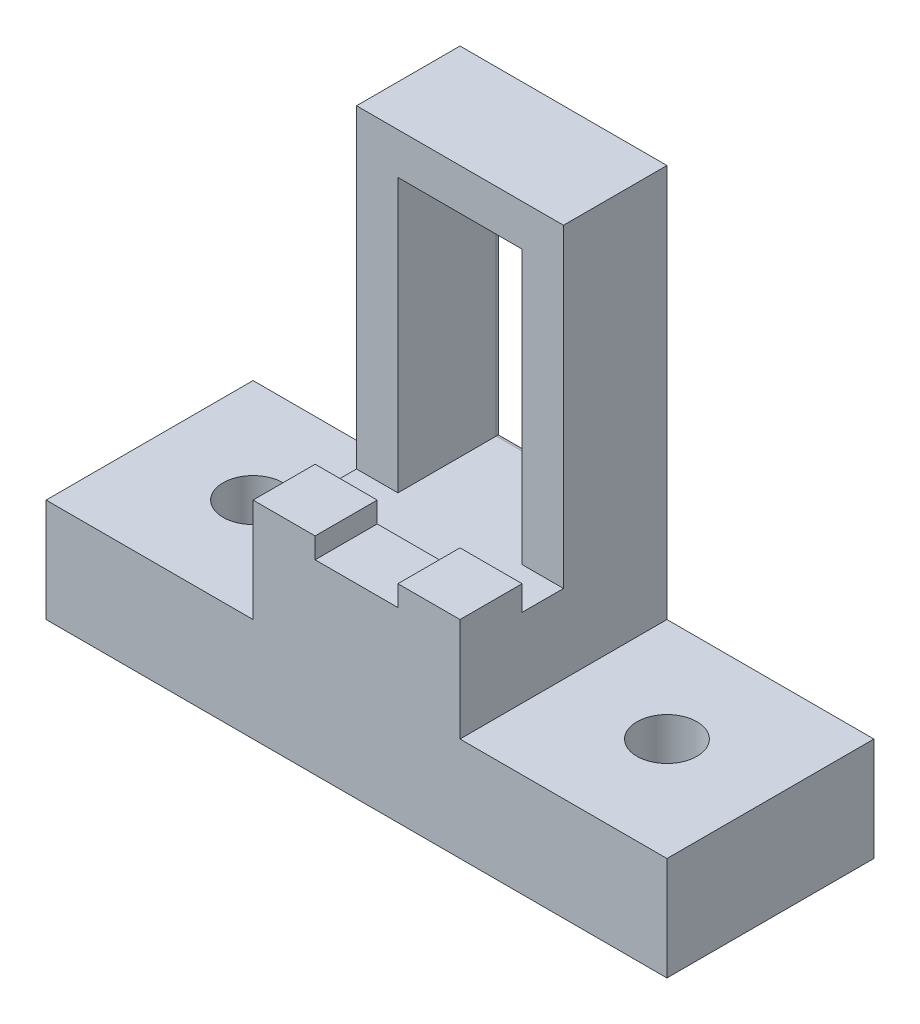
SolidWorks part; units mm, degrees
other "标注1"
sketch "草图8" plane through (-30, 24, -10.05) normal (-0.0333, 0.0376, -0.9987) x (-0.9561, 0.2897, 0.0428)
sketch "草图10" plane through (-30, 24, -10.05) normal (-0.0333, 0.0376, -0.9987) x (-0.9561, 0.2897, 0.0428)
sketch "草图23" plane through (-30, 24, -10) normal (-0.0333, 0.0376, -0.9987) x (-0.9561, 0.2897, 0.0428)
sketch "草图26" plane through (-30, 24, -10) normal (-0.0333, 0.0376, -0.9987) x (-0.9561, 0.2897, 0.0428)
sketch "草图30" plane through (-30, 24, -10) normal (-0.0333, 0.0376, -0.9987) x (-0.9561, 0.2897, 0.0428)
other "标注2"
sketch "草图16" plane through (0, 24, 0) normal (0.8795, 0.3038, 0.3663) x (0.4513, -0.2881, -0.8446)
sketch "草图24" plane through (0, 24, 0) normal (0.8795, 0.3038, 0.3663) x (0.4513, -0.2881, -0.8446)
sketch "草图27" plane through (0, 24, 0) normal (0.8795, 0.3038, 0.3663) x (0.4513, -0.2881, -0.8446)
sketch "草图31" plane through (0, 24, 0) normal (0.8795, 0.3038, 0.3663) x (0.4513, -0.2881, -0.8446)
other "标注3"
sketch "草图17" plane through (0, 24, 0) normal (0.8795, 0.3038, 0.3663) x (0.4513, -0.2881, -0.8446)
sketch "草图25" plane through (0, 24, 0) normal (0.8795, 0.3038, 0.3663) x (0.4513, -0.2881, -0.8446)
sketch "草图28" plane through (0, 24, 0) normal (0.8795, 0.3038, 0.3663) x (0.4513, -0.2881, -0.8446)
sketch "草图32" plane through (0, 24, 0) normal (0.8795, 0.3038, 0.3663) x (0.4513, -0.2881, -0.8446)
ref_plane "前视基准面" through (0, 0, 0) normal (0, 0, 1) x (1, 0, 0)
ref_plane "上视基准面" through (0, 0, 0) normal (0, 1, 0) x (1, 0, 0)
ref_plane "右视基准面" through (0, 0, 0) normal (1, 0, 0) x (0, 0, -1)
other "Configuration Table"
sketch "草图1" plane through (0, 0, 0) normal (0, 1, 0) x (1, 0, 0)
  line L0 (-20, 0) -> (-20, -5)
  line L2 (0, 0) -> (0, 10)
  line L3 (0, 10) -> (-30, 10)
  line L4 (-30, 0) -> (-30, 10)
  line L5 (-20, -5) -> (-10, -5)
  line L6 (-10, -5) -> (-10, 0)
  line L7 (-30, 0) -> (-20, 0)
  line L8 (-10, 0) -> (0, 0)
  dimension "D1" = 10
  dimension "D2" = 30
  dimension "D3" = 10
  dimension "D4" = 10
  dimension "D5" = 5
  dimension "D6" = 5
extrude "凸台-拉伸1" add sketch "草图1" along normal blind 4
sketch "草图2" plane through (0, 4, 0) normal (0, 1, 0) x (1, 0, 0)
  line L7 (0, 10) -> (-30, 10) construction
  line L8 (-20, -5) -> (-10, -5)
  line L9 (-20, -5) -> (-20, 10)
  line L10 (-20, 10) -> (-10, 10)
  line L11 (-10, -5) -> (-10, 10)
extrude "凸台-拉伸2" add sketch "草图2" along normal blind 20
sketch "草图3" plane through (0, 4, 0) normal (0, 1, 0) x (1, 0, 0)
  line L0 (-20, 10) -> (-30, 10) construction
  line L1 (-30, 10) -> (-30, 0) construction
  line L2 (0, 10) -> (-10, 10) construction
  line L3 (0, 0) -> (0, 10) construction
  circle A0 centre (-25, 5) radius 1.45
  circle A1 centre (-5, 5) radius 1.45
  dimension "D1" = 5
  dimension "D2" = 5
  dimension "D3" = 5
  dimension "D4" = 5
  dimension "D5" = 2.9
  dimension "D6" = 2.9
extrude "切除-拉伸1" cut sketch "草图3" against normal blind 20
sketch "草图4" plane through (0, 0, -10) normal (0, 0, -1) x (-1, 0, 0)
  line L6 (10, 24) -> (10, 4) construction
  line L7 (12, 22) -> (18, 22)
  line L8 (12, 22) -> (12, 8.8)
  line L9 (12, 8.8) -> (18, 8.8)
  line L10 (18, 22) -> (18, 8.8)
  line L11 (10, 24) -> (20, 24) construction
  dimension "D1" = 6
  dimension "D2" = 13.2
  dimension "D3" = 2
  dimension "D4" = 2
extrude "切除-拉伸2" cut sketch "草图4" against normal blind 9.5
sketch "草图6" plane through (0, 0, -0.5) normal (0, 0, -1) x (-1, 0, 0)
  line L0 (15, 22) -> (15, 20.68) construction
  line L1 (18, 22) -> (12, 22) construction
  line L2 (15, 20.68) -> (15, 15.6) construction
  line L3 (15, 15.6) -> (15, 10.52) construction
  circle A0 centre (15, 20.68) radius 0.75
  circle A2 centre (15, 10.52) radius 0.75
  circle A3 centre (15, 15.6) radius 0.75
  dimension "D4" = 1.5
  dimension "D5" = 1.5
  dimension "D6" = 1.5
  dimension "D1" = 1.32
  dimension "D2" = 5.08
  dimension "D3" = 5.08
extrude "切除-拉伸4" cut sketch "草图6" against normal blind 3.5
sketch "草图7" plane through (0, 0, 5) normal (0, 0, 1) x (1, 0, 0)
  line L4 (-10, 24) -> (-20, 24)
  line L5 (-20, 24) -> (-20, 0)
  line L6 (-20, 0) -> (-10, 0)
  line L7 (-10, 0) -> (-10, 24)
  line L8 (-10, 24) -> (-20, 24)
  line L9 (-20, 24) -> (-20, 0)
  line L10 (-20, 0) -> (-10, 0)
  line L11 (-10, 0) -> (-10, 24)
  dimension "D1" = 0
extrude "切除-拉伸5" cut sketch "草图7" against normal blind 5
sketch "草图9" plane through (0, 0, -0.5) normal (0, 0, -1) x (-1, 0, 0)
  line L1 (13.5, 21.6) -> (16.5, 21.6)
  line L2 (13.5, 21.6) -> (13.5, 9.6)
  line L3 (13.5, 9.6) -> (16.5, 9.6)
  line L4 (16.5, 21.6) -> (16.5, 9.6)
  line L5 (13.5, 21.6) -> (16.5, 9.6) construction
  line L6 (13.5, 9.6) -> (16.5, 21.6) construction
  point P0 (15, 15.6)
  dimension "D1" = 3
  dimension "D2" = 12
extrude "切除-拉伸6" cut sketch "草图9" against normal blind 10
sketch "草图11" plane through (0, 0, -0.5) normal (0, 0, -1) x (-1, 0, 0)
  line L0 (18, 8.8) -> (18, 22) construction
  line L1 (16.5, 21.6) -> (18, 21.6)
  line L2 (16.5, 21.6) -> (16.5, 9.6)
  line L3 (16.5, 9.6) -> (18, 9.6)
  line L4 (18, 21.6) -> (18, 9.6)
  line L5 (12, 22) -> (12, 8.8) construction
  line L6 (13.5, 21.6) -> (12, 21.6)
  line L7 (13.5, 21.6) -> (13.5, 9.6)
  line L8 (13.5, 9.6) -> (12, 9.6)
  line L9 (12, 21.6) -> (12, 9.6)
extrude "切除-拉伸7" cut sketch "草图11" against normal blind 10
sketch "草图13" plane through (0, 24, 0) normal (0, 1, 0) x (1, 0, 0)
  line L0 (-10, 0) -> (-10, 10) construction
  line L1 (-20, 0) -> (-10, 0)
  line L2 (-20, 0) -> (-20, 5)
  line L3 (-20, 5) -> (-10, 5)
  line L4 (-10, 0) -> (-10, 5)
extrude "切除-拉伸8" cut sketch "草图13" against normal up to surface (20 mm away) up to face at (-5, 4, -3.55)
sketch "草图19" plane through (0, 4, 0) normal (0, 1, 0) x (1, 0, 0)
  line L1 (-20, 5) -> (-10, 5)
  line L2 (-20, 5) -> (-20, 2.6)
  line L3 (-20, 2.6) -> (-10, 2.6)
  line L4 (-10, 5) -> (-10, 2.6)
  dimension "D1" = 2.4
extrude "凸台-拉伸6" add sketch "草图19" along normal blind 4.8
sketch "草图20" plane through (0, 4, 0) normal (0, 1, 0) x (1, 0, 0)
  line L0 (-30, 0) -> (0, 0) construction
  line L1 (-20, 2.6) -> (-10, 2.6)
  line L2 (-20, 2.6) -> (-20, 0)
  line L3 (-20, 0) -> (-10, 0)
  line L4 (-10, 2.6) -> (-10, 0)
extrude "凸台-拉伸7" add sketch "草图20" along normal blind 6
fillet "圆角17" radius 0.25 4 edges at (-15, 8.8, -10) (-15, 22, -10) (-18, 15.4, -10) (-12, 15.4, -10)
sketch "草图21" plane through (0, 0, 0) normal (0, 0, 1) x (1, 0, 0)
  line L0 (-15, 10) -> (-15, 7.5151) construction
  line L1 (-20, 10) -> (-10, 10) construction
  line L2 (-13, 10) -> (-17, 10)
  line L3 (-17, 10) -> (-17, 9)
  line L4 (-17, 9) -> (-13, 9)
  line L5 (-13, 10) -> (-13, 9)
  point P9 (-15, 9)
  dimension "D1" = 2
  dimension "D2" = 1
extrude "切除-拉伸9" cut sketch "草图21" against normal blind 5.2
sketch "草图22" plane through (0, 0, -2.6) normal (0, 0, -1) x (-1, 0, 0)
  line L8 (17, 9) -> (13, 9)
  line L9 (13, 9) -> (13, 10)
  line L10 (13, 10) -> (10, 10)
  line L11 (10, 10) -> (10, 8.8)
  line L12 (10, 8.8) -> (20, 8.8)
  line L13 (20, 8.8) -> (20, 10)
  line L14 (20, 10) -> (17, 10)
  line L15 (17, 10) -> (17, 9)
  line L16 (17, 9) -> (13, 9)
  line L17 (13, 9) -> (13, 10)
  line L18 (13, 10) -> (10, 10)
  line L19 (10, 10) -> (10, 8.8)
  line L20 (10, 8.8) -> (20, 8.8)
  line L21 (20, 8.8) -> (20, 10)
  line L22 (20, 10) -> (17, 10)
  line L23 (17, 10) -> (17, 9)
  dimension "D1" = 0
extrude "凸台-拉伸8" add sketch "草图22" along normal blind 0.4
sketch "草图29" plane through (0, 4, 0) normal (0, 1, 0) x (1, 0, 0)
  line L0 (-30, 0) -> (-20, 0) construction
  line L1 (-20, 0) -> (-20, 10) construction
  line L2 (-20, 10) -> (-30, 10) construction
  line L3 (-30, 10) -> (-30, 0) construction
  line L4 (-10, 10) -> (-10, 0) construction
  line L5 (-10, 0) -> (0, 0) construction
  line L6 (0, 0) -> (0, 10) construction
  line L7 (0, 10) -> (-10, 10) construction
  line L8 (-30, 0) -> (-20, 0)
  line L9 (-20, 0) -> (-20, 10)
  line L10 (-20, 10) -> (-30, 10)
  line L11 (-30, 10) -> (-30, 0)
  line L12 (-10, 10) -> (-10, 0)
  line L13 (-10, 0) -> (0, 0)
  line L14 (0, 0) -> (0, 10)
  line L15 (0, 10) -> (-10, 10)
  circle A0 centre (-5, 5) radius 1.45 construction
  circle A1 centre (-25, 5) radius 1.45 construction
  circle A2 centre (-5, 5) radius 1.45
  circle A3 centre (-25, 5) radius 1.45
extrude "凸台-拉伸9" add sketch "草图29" along normal blind 1
